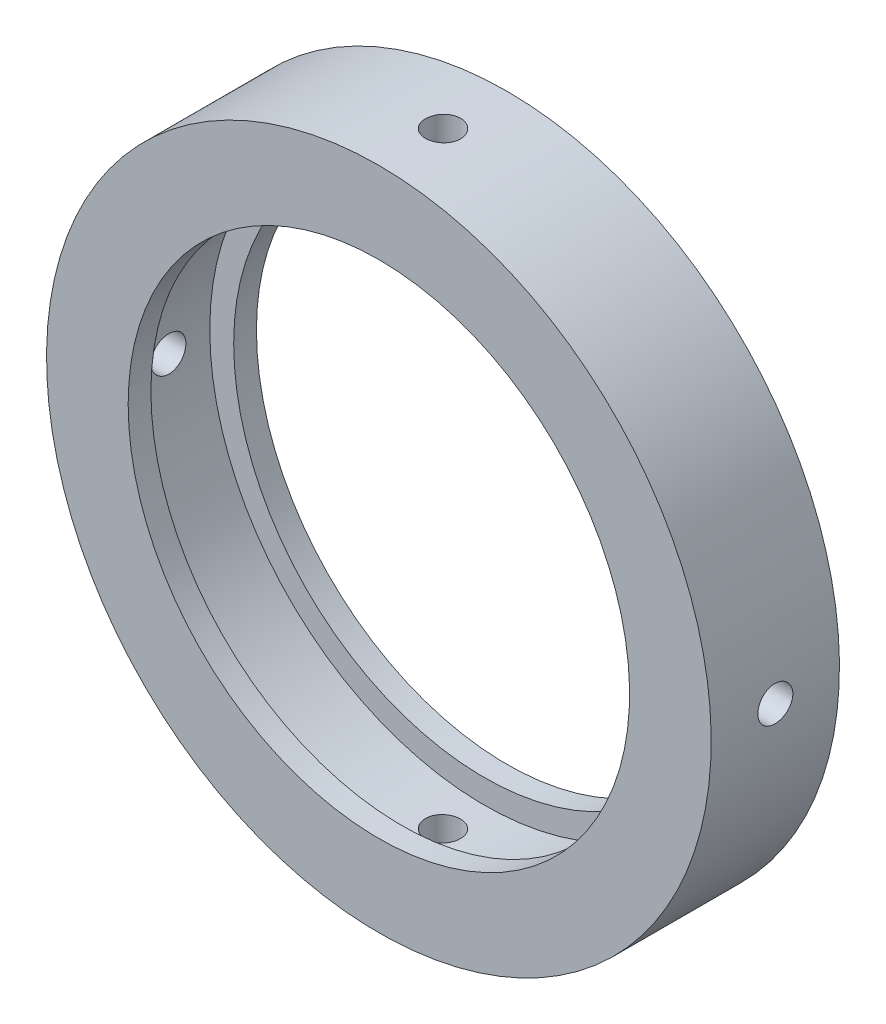
SolidWorks part; units mm, degrees
ref_plane "Front Plane" through (0, 0, 0) normal (1, 0, 0) x (0, 1, 0)
ref_plane "Top Plane" through (0, 0, 0) normal (0, 0, 1) x (0, 1, 0)
ref_plane "Right Plane" through (0, 0, 0) normal (0, 1, 0) x (-1, 0, 0)
sketch "Sketch1" plane through (0, 0, 0) normal (0, 0, 1) x (0, 1, 0)
  circle A0 centre (0, 0) radius 23.5
  dimension "D1" = 47
extrude "Extrude-Thin1" add sketch "Sketch1" along normal blind 11 thin
sketch "Sketch2" plane through (0, 0, 0) normal (0, 0, -1) x (1, 0, 0)
  circle A0 centre (0, 0) radius 23.55
  dimension "D1" = 47.1
extrude "Cut-Extrude1" cut sketch "Sketch2" against normal blind 7.1 from offset 1.95 offset against normal yes
sketch "Sketch3" plane through (0, 0, 0) normal (1, 0, 0) x (0, 1, 0)
  circle A0 centre (0, 5.5) radius 1.5
  dimension "D1" = 3
  dimension "D2" = 5.5
extrude "Cut-Extrude2" cut sketch "Sketch3" against normal through all both and the other way through all
pattern_circular "CirPattern1" count 2 every 90 about axis through (0, 0, 9.05) along (0, 0, -1) of "Cut-Extrude2"
